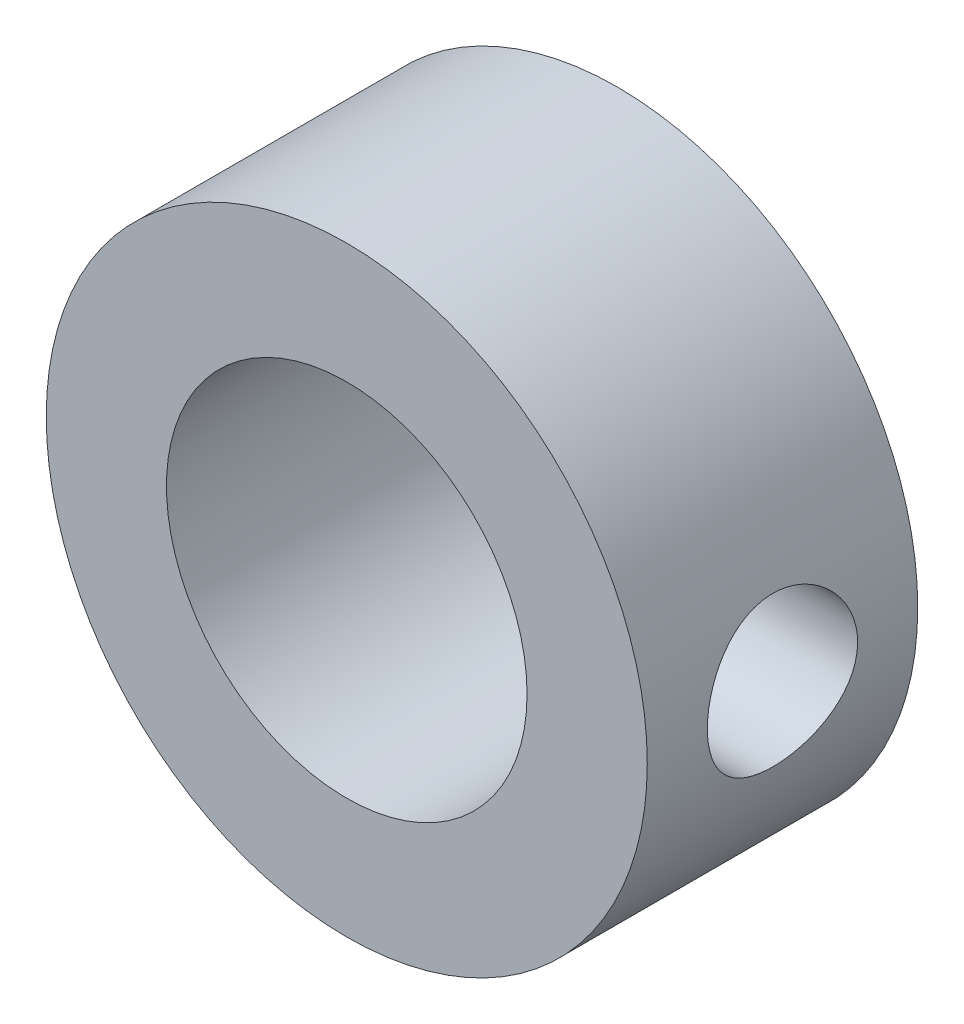
SolidWorks part; units mm, degrees
material "AISI 316 Barra de acero inoxidable recocido (SS)"
ref_plane "Alzado" through (0, 0, 0) normal (0, 0, 1) x (1, 0, 0)
ref_plane "Planta" through (0, 0, 0) normal (0, 1, 0) x (1, 0, 0)
ref_plane "Vista lateral" through (0, 0, 0) normal (1, 0, 0) x (0, 0, -1)
sketch "Croquis1" plane through (0, 0, 0) normal (1, 0, 0) x (0, 0, -1)
  line L0 (0, 0) -> (61.9918, 0) construction
  line L1 (0, 0) -> (0, 15.875)
  line L2 (0, 15.875) -> (14.288, 15.875)
  line L3 (14.288, 15.875) -> (14.288, 0)
  line L4 (14.288, 0) -> (0, 0)
  dimension "D1" = 14.288
  dimension "D2" = 31.75
revolve "Revolución1" add sketch "Croquis1" angle 360 about L0
sketch "Croquis2" plane through (0, 0, 0) normal (0, 0, 1) x (1, 0, 0)
  circle A0 centre (0, 0) radius 9.525
  dimension "D1" = 19.05
extrude "Cortar-Extruir1" cut sketch "Croquis2" against normal up to next
hole_wizard "Taladro roscado 1/8-27 NPSM1" positions "Croquis3D1" profile "Croquis3" tap size "1/8-27 NPSM" standard "Ansi Inch"
sketch3d "Croquis3D1"
  line L1 (0, 0, 0) -> (0, 0, -14.288) construction
  line L2 (0, 0, -14.288) -> (0, 0, 0) construction
  line L3 (0, 0, -14.288) -> (0, 0, 0) construction
  line L5 (0, 0, -7.144) -> (15.875, 0, -7.144) construction
  point P18 (0, 0, -7.144)
  point P21 (0, 0, -7.144)
  point P27 (15.875, 0, -7.144)
cosmetic thread "Rosca de taladro1"
sketch "Croquis3" plane through (15.875, 0, -7.144) normal (0, 1, 0) x (0, 0, -1)
  line L0 (0, 0) -> (0, 15.875)
  line L1 (0, 15.875) -> (3.9687, 15.875)
  line L2 (3.9687, 15.875) -> (3.9687, 0)
  line L5 (3.9687, 0) -> (0, 0)
  line L11 (0, -6.35) -> (0, 107.95) construction
  dimension "Diámetro de perforador para roscar hasta el siguiente" = 7.9375
  dimension "Profundidad de perforador para roscar hasta el siguiente" = 15.875
